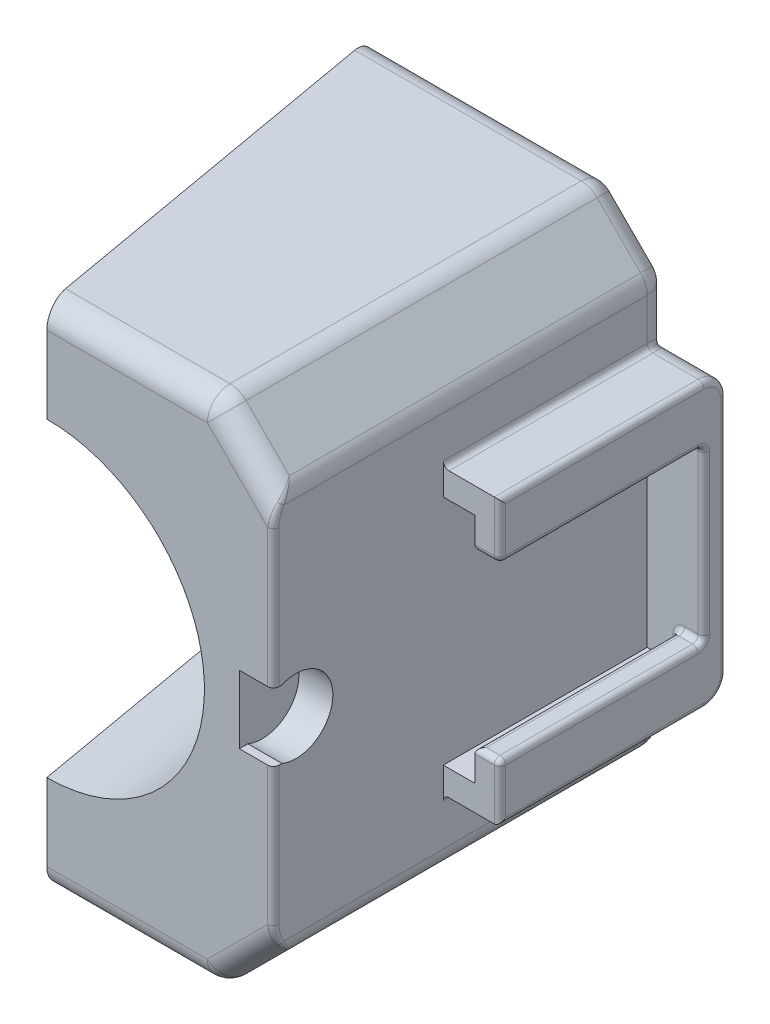
SolidWorks part; units mm, degrees
ref_plane "Front Plane" through (0, 0, 0) normal (0, 0, 1) x (1, 0, 0)
ref_plane "Top Plane" through (0, 0, 0) normal (0, 1, 0) x (1, 0, 0)
ref_plane "Right Plane" through (0, 0, 0) normal (1, 0, 0) x (0, 0, -1)
sketch "Sketch1" plane through (0, 0, 0) normal (0, 1, 0) x (1, 0, 0)
  line L0 (0, 0) -> (-31.1714, 0)
  line L1 (-31.1714, 0) -> (-25, -35)
  line L2 (-25, -35) -> (0, -35)
  line L3 (0, -35) -> (0, 0)
  dimension "D1" = 80
  dimension "D2" = 35
  dimension "D3" = 25
extrude "Boss-Extrude1" add sketch "Sketch1" along normal blind 45
ref_plane "Plane1" through (5.2315, 0, 29.6694) normal (-0.1736, 0, -0.9848) x (-0.9848, 0, 0.1736)
sketch "Sketch2" plane through (5.2315, 0, 29.6694) normal (-0.1736, 0, -0.9848) x (-0.9848, 0, 0.1736)
  line L0 (30.6979, 45) -> (30.6979, 0) construction
  circle A0 centre (30.6979, 22.5) radius 13.7
  dimension "D1" = 27.4
extrude "Cut-Extrude1" cut sketch "Sketch2" against normal through all and the other way through all
ref_plane "Plane2" through (0, 0, 35) normal (0, 0, 1) x (1, 0, 0)
sketch "Sketch3" plane through (0, 0, 35) normal (0, 0, 1) x (1, 0, 0)
  line L0 (-5, 35) -> (-5, 40)
  line L1 (-25, 45) -> (0, 45) construction
  line L4 (-5, 35) -> (0, 35)
  line L5 (0, 45) -> (0, 0) construction
  line L6 (0, 35) -> (0, 45)
  line L7 (-10, 45) -> (0, 45)
  line L8 (-5, 40) -> (-10, 45)
  line L12 (-5, 10) -> (0, 10)
  line L13 (0, 10) -> (0, 0)
  line L14 (0, 0) -> (-10, 0)
  line L15 (-25, 0) -> (0, 0) construction
  line L16 (-10, 0) -> (-5, 5)
  line L17 (-5, 5) -> (-5, 10)
  dimension "D1" = 25
  dimension "D3" = 5
  dimension "D4" = 5
extrude "Cut-Extrude2" cut sketch "Sketch3" against normal through all
sketch "Sketch4" plane through (0, 0, 35) normal (0, 0, 1) x (1, 0, 0)
  line L1 (-5, 35) -> (0, 35)
  line L2 (-5, 35) -> (-5, 10)
  line L3 (-5, 10) -> (0, 10)
  line L4 (0, 35) -> (0, 10)
extrude "Cut-Extrude3" cut sketch "Sketch4" against normal blind 15
ref_plane "Plane3" through (0, 0, 20) normal (0, 0, 1) x (1, 0, 0)
sketch "Sketch5" plane through (0, 0, 20) normal (0, 0, 1) x (1, 0, 0)
  line L0 (-5, 32.75) -> (-2.2, 32.75)
  line L1 (-5, 35) -> (-5, 10) construction
  line L2 (-2.2, 32.75) -> (-2.2, 30)
  line L3 (-2.2, 30) -> (0, 30)
  line L4 (0, 10) -> (0, 35) construction
  line L5 (0, 30) -> (0, 15)
  line L6 (0, 15) -> (-2.2, 15)
  line L7 (-2.2, 15) -> (-2.2, 12.25)
  line L8 (-2.2, 12.25) -> (-5, 12.25)
  line L9 (-5, 12.25) -> (-5, 32.75)
  line L10 (0, 35) -> (0, 30) construction
  line L11 (0, 15) -> (0, 10) construction
  point P4 (0, 22.5)
  dimension "D1" = 2.2
  dimension "D2" = 20.5
  dimension "D3" = 15
extrude "Cut-Extrude4" cut sketch "Sketch5" against normal offset from surface (18 mm away) 2 up to face at (-12.5645, 22.5, 0)
ref_plane "Plane4" through (-5, 0, 0) normal (1, 0, 0) x (0, 0, -1)
sketch "Sketch6" plane through (-5, 0, 0) normal (1, 0, 0) x (0, 0, -1)
  line L0 (-35, 19.5) -> (-35, 25.5)
  line L1 (-35, 25.5) -> (-34.25, 25.5)
  line L2 (-35, 19.5) -> (-34.25, 19.5)
  line L3 (-35, 40) -> (-35, 5) construction
  line L5 (-29.75, 5) -> (-29.75, 40) construction
  line L6 (0, 5) -> (-35, 5) construction
  line L7 (0, 40) -> (-35, 40) construction
  line L8 (-2, 12.25) -> (-2, 32.75) construction
  arc A0 (-34.25, 19.5) -> (-34.25, 25.5) centre (-33, 22.5) ccw
  point P11 (-29.75, 22.5)
  dimension "D1" = 3.25
  dimension "D2" = 31
  dimension "D3" = 6
extrude "Cut-Extrude5" cut sketch "Sketch6" against normal blind 3
ref_plane "Plane5" through (-30.2315, 0, 5.3306) normal (-0.9848, 0, 0.1736) x (0.1736, 0, 0.9848)
sketch "Sketch8" plane through (-30.2315, 0, 5.3306) normal (-0.9848, 0, 0.1736) x (0.1736, 0, 0.9848)
  line L0 (2.3571, 40.2) -> (2.3571, 4.8) construction
  line L1 (33.0791, 25.5) -> (33.0791, 19.5) construction
  line L2 (-5.4129, 45) -> (30.1271, 45) construction
  line L3 (2.3571, 40.2) -> (22.3571, 40.2) construction
  line L4 (-5.4129, 36.2) -> (30.1271, 36.2) construction
  circle A0 centre (2.3571, 40.2) radius 2.1
  circle A1 centre (22.3571, 40.2) radius 2.1
  circle A2 centre (22.3571, 4.8) radius 2.1
  circle A3 centre (2.3571, 4.8) radius 2.1
  point P8 (2.3571, 22.5)
  point P9 (12.3571, 45)
  point P10 (12.3571, 40.2)
  point P16 (33.0791, 22.5)
  dimension "D3" = 4.2
  dimension "D1" = 20
  dimension "D2" = 4
extrude "Cut-Extrude6" cut sketch "Sketch8" against normal blind 15
fillet "Fillet1" radius 2 16 edges at (-7.5, 2.5, 35) (-17.5, 0, 35) (-17.5, 45, 35) (-20.5857, 0, 0) (-10, 0, 17.5) (-5, 5, 17.5) (-5, 7.5, 0) (-7.5, 2.5, 0) (-5, 37.5, 0) (-7.5, 42.5, 0) (-20.5857, 45, 0) (-10, 45, 17.5) (-5, 40, 17.5) (-7.5, 42.5, 35) (-2.5, 35, 0) (-2.5, 10, 0)
fillet "Fillet2" radius 0.5 28 edges at (-2.2, 31.375, 2) (0, 22.5, 2) (-2.2, 13.625, 2) (-2.2, 30, 11) (-1.1, 30, 20) (0, 30, 11) (0, 15, 11) (-1.1, 15, 20) (-2.2, 15, 11) (-1.1, 30, 2) (-1.1, 15, 2) (0, 32.5, 20) (0, 12.5, 20) (0, 35, 11) (0, 22.5, 0) (0, 10, 11) (0, 34.4142, 0.5858) (0, 10.5858, 0.5858) (-5.1522, 5.0631, 33.7654) (-5, 6.746, 34.8478) (-5.1522, 39.9369, 33.7654) (-5, 38.254, 34.8478) (-5.5858, 34.4142, 0.5858) (-5.5858, 10.5858, 0.5858) (-5, 13.6642, 35) (-5, 31.3358, 35) (-5, 35, 11) (-5, 10, 11)
